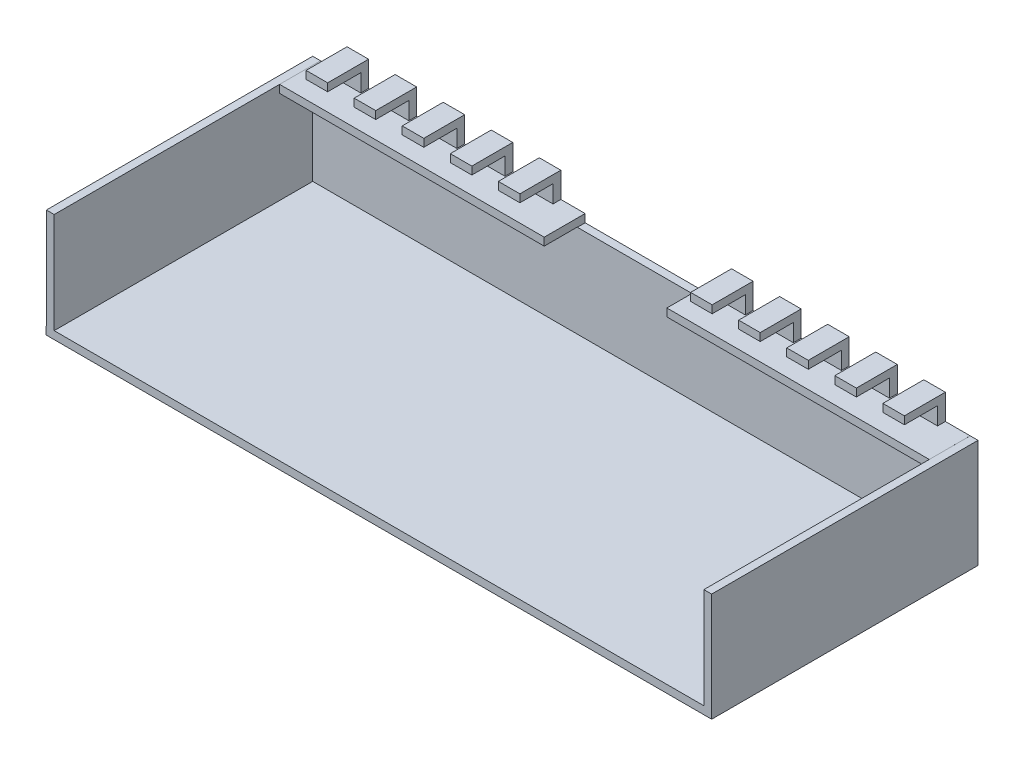
SolidWorks part; units mm, degrees
ref_plane "Plan de face" through (0, 0, 0) normal (0, 0, 1) x (1, 0, 0)
ref_plane "Plan de dessus" through (0, 0, 0) normal (0, 1, 0) x (1, 0, 0)
ref_plane "Plan de droite" through (0, 0, 0) normal (1, 0, 0) x (0, 0, -1)
sketch "Esquisse1" plane through (0, 0, 0) normal (0, 0, 1) x (1, 0, 0)
  line L0 (0, 0) -> (122.5, 0)
  line L1 (122.5, 0) -> (122.5, -5.3)
  line L2 (122.5, -5.3) -> (-73.5, -5.3)
  line L3 (-73.5, -5.3) -> (-73.5, 0)
  line L4 (-73.5, 0) -> (0, 0)
  line L5 (-73.5, 0) -> (-73.5, 2.35)
  line L6 (-73.5, 2.35) -> (122.5, 2.35)
  line L7 (122.5, 2.35) -> (122.5, 0)
  line L8 (122.5, -5.3) -> (122.5, -7.65)
  line L9 (122.5, -7.65) -> (-73.5, -7.65)
  line L10 (-73.5, -7.65) -> (-73.5, -5.3)
  dimension "D1" = 5.3
  dimension "D2" = 2.35
  dimension "D3" = 2.35
  dimension "D4" = 196
extrude "Boss.-Extru.1" add sketch "Esquisse1" along normal blind 10 contours L7 L6 L5 L4 L0 | L10 L9 L8 L2
sketch "Esquisse2" plane through (0, 0, 0) normal (0, 0, -1) x (-1, 0, 0)
  line L0 (-122.5, 2.35) -> (-122.5, -35.65)
  line L1 (73.5, 2.35) -> (73.5, -35.65)
  line L2 (73.5, -35.65) -> (-122.5, -35.65)
  line L3 (-122.5, 2.35) -> (73.5, 2.35)
  dimension "D1" = 38
extrude "Boss.-Extru.2" add sketch "Esquisse2" along normal blind 2.35
sketch "Esquisse3" plane through (-73.5, 0, 0) normal (-1, 0, 0) x (0, 0, 1)
  line L0 (-2.35, -5.3036) -> (78, -5.3036)
  line L1 (-2.35, -5.3036) -> (-2.35, -35.65)
  line L2 (-2.35, -35.65) -> (78, -35.65)
  line L3 (78, -35.65) -> (78, -5.3036)
  dimension "D1" = 80.35
extrude "Boss.-Extru.4" add sketch "Esquisse3" along normal blind 2.35
sketch "Esquisse5" plane through (122.5, 0, 0) normal (1, 0, 0) x (0, 0, -1)
  line L0 (-78, -5.3) -> (2.35, -5.3036)
  line L1 (2.35, -5.3036) -> (2.35, -35.65)
  line L2 (2.35, -35.65) -> (-78, -35.65)
  line L3 (-78, -35.65) -> (-78, -5.3)
  dimension "D1" = 80.35
extrude "Boss.-Extru.5" add sketch "Esquisse5" along normal blind 2.35
sketch "Esquisse6" plane through (0, 0, 10) normal (0, 0, 1) x (1, 0, 0)
  line L0 (-75.9651, -35.65) -> (-75.9651, -38)
  line L1 (124.85, -35.65) -> (-75.9651, -35.65)
  line L2 (-75.9651, -38) -> (124.85, -38)
  line L3 (124.85, -38) -> (124.85, -35.65)
  line L6 (124.85, -5.3) -> (124.85, -35.65) construction
  dimension "D1" = 2.35
  dimension "D2" = 0
extrude "Boss.-Extru.6" add sketch "Esquisse6" against normal blind 12.35 and the other way blind 68
sketch "Esquisse7" plane through (0, 0, 10) normal (0, 0, 1) x (1, 0, 0)
  line L0 (-73.5, 2.35) -> (-73.5, -5.3)
  line L1 (-73.5, -5.3) -> (-65.5, -5.3)
  line L2 (122.5, -5.3) -> (-73.5, -5.3) construction
  line L3 (-65.5, -5.3) -> (-65.5, 2.35)
  line L4 (-73.5, 2.35) -> (122.5, 2.35) construction
  line L5 (-65.5, 2.35) -> (-73.5, 2.35)
  line L6 (-51, 2.35) -> (-59, 2.35)
  line L7 (-59, 2.35) -> (-59, -5.3)
  line L8 (-59, -5.3) -> (-51, -5.3)
  line L9 (-51, -5.3) -> (-51, 2.35)
  line L10 (-36.5, 2.35) -> (-44.5, 2.35)
  line L11 (-44.5, 2.35) -> (-44.5, -5.3)
  line L12 (-44.5, -5.3) -> (-36.5, -5.3)
  line L13 (-36.5, -5.3) -> (-36.5, 2.35)
  line L14 (-22, 2.35) -> (-30, 2.35)
  line L15 (-30, 2.35) -> (-30, -5.3)
  line L16 (-30, -5.3) -> (-22, -5.3)
  line L17 (-22, -5.3) -> (-22, 2.35)
  line L18 (-7.5, 2.35) -> (-15.5, 2.35)
  line L19 (-15.5, 2.35) -> (-15.5, -5.3)
  line L20 (-15.5, -5.3) -> (-7.5, -5.3)
  line L21 (-7.5, -5.3) -> (-7.5, 2.35)
  line L22 (7, 2.35) -> (-1, 2.35)
  line L23 (-1, 2.35) -> (-1, -5.3)
  line L24 (-1, -5.3) -> (7, -5.3)
  line L25 (7, -5.3) -> (7, 2.35)
  line L26 (21.5, 2.35) -> (13.5, 2.35)
  line L27 (13.5, 2.35) -> (13.5, -5.3)
  line L28 (13.5, -5.3) -> (21.5, -5.3)
  line L29 (21.5, -5.3) -> (21.5, 2.35)
  line L30 (36, 2.35) -> (28, 2.35)
  line L31 (28, 2.35) -> (28, -5.3)
  line L32 (28, -5.3) -> (36, -5.3)
  line L33 (36, -5.3) -> (36, 2.35)
  line L34 (50.5, 2.35) -> (42.5, 2.35)
  line L35 (42.5, 2.35) -> (42.5, -5.3)
  line L36 (42.5, -5.3) -> (50.5, -5.3)
  line L37 (50.5, -5.3) -> (50.5, 2.35)
  line L38 (65, 2.35) -> (57, 2.35)
  line L39 (57, 2.35) -> (57, -5.3)
  line L40 (57, -5.3) -> (65, -5.3)
  line L41 (65, -5.3) -> (65, 2.35)
  line L42 (79.5, 2.35) -> (71.5, 2.35)
  line L43 (71.5, 2.35) -> (71.5, -5.3)
  line L44 (71.5, -5.3) -> (79.5, -5.3)
  line L45 (79.5, -5.3) -> (79.5, 2.35)
  line L46 (94, 2.35) -> (86, 2.35)
  line L47 (86, 2.35) -> (86, -5.3)
  line L48 (86, -5.3) -> (94, -5.3)
  line L49 (94, -5.3) -> (94, 2.35)
  line L50 (108.5, 2.35) -> (100.5, 2.35)
  line L51 (100.5, 2.35) -> (100.5, -5.3)
  line L52 (100.5, -5.3) -> (108.5, -5.3)
  line L53 (108.5, -5.3) -> (108.5, 2.35)
  line L54 (123, 2.35) -> (115, 2.35)
  line L55 (115, 2.35) -> (115, -5.3)
  line L56 (115, -5.3) -> (123, -5.3)
  line L57 (123, -5.3) -> (123, 2.35)
  line L58 (137.5, 2.35) -> (129.5, 2.35)
  line L59 (129.5, 2.35) -> (129.5, -5.3)
  line L60 (129.5, -5.3) -> (137.5, -5.3)
  line L61 (137.5, -5.3) -> (137.5, 2.35)
  line L62 (152, 2.35) -> (144, 2.35)
  line L63 (144, 2.35) -> (144, -5.3)
  line L64 (144, -5.3) -> (152, -5.3)
  line L65 (152, -5.3) -> (152, 2.35)
  line L66 (166.5, 2.35) -> (158.5, 2.35)
  line L67 (158.5, 2.35) -> (158.5, -5.3)
  line L68 (158.5, -5.3) -> (166.5, -5.3)
  line L69 (166.5, -5.3) -> (166.5, 2.35)
  line L70 (181, 2.35) -> (173, 2.35)
  line L71 (173, 2.35) -> (173, -5.3)
  line L72 (173, -5.3) -> (181, -5.3)
  line L73 (181, -5.3) -> (181, 2.35)
  line L74 (195.5, 2.35) -> (187.5, 2.35)
  line L75 (187.5, 2.35) -> (187.5, -5.3)
  line L76 (187.5, -5.3) -> (195.5, -5.3)
  line L77 (195.5, -5.3) -> (195.5, 2.35)
  line L78 (210, 2.35) -> (202, 2.35)
  line L79 (202, 2.35) -> (202, -5.3)
  line L80 (202, -5.3) -> (210, -5.3)
  line L81 (210, -5.3) -> (210, 2.35)
  line L82 (224.5, 2.35) -> (216.5, 2.35)
  line L83 (216.5, 2.35) -> (216.5, -5.3)
  line L84 (216.5, -5.3) -> (224.5, -5.3)
  line L85 (224.5, -5.3) -> (224.5, 2.35)
  line L86 (239, 2.35) -> (231, 2.35)
  line L87 (231, 2.35) -> (231, -5.3)
  line L88 (231, -5.3) -> (239, -5.3)
  line L89 (239, -5.3) -> (239, 2.35)
  line L90 (253.5, 2.35) -> (245.5, 2.35)
  line L91 (245.5, 2.35) -> (245.5, -5.3)
  line L92 (245.5, -5.3) -> (253.5, -5.3)
  line L93 (253.5, -5.3) -> (253.5, 2.35)
  line L94 (268, 2.35) -> (260, 2.35)
  line L95 (260, 2.35) -> (260, -5.3)
  line L96 (260, -5.3) -> (268, -5.3)
  line L97 (268, -5.3) -> (268, 2.35)
  line L98 (282.5, 2.35) -> (274.5, 2.35)
  line L99 (274.5, 2.35) -> (274.5, -5.3)
  line L100 (274.5, -5.3) -> (282.5, -5.3)
  line L101 (282.5, -5.3) -> (282.5, 2.35)
  line L102 (297, 2.35) -> (289, 2.35)
  line L103 (289, 2.35) -> (289, -5.3)
  line L104 (289, -5.3) -> (297, -5.3)
  line L105 (297, -5.3) -> (297, 2.35)
  line L106 (311.5, 2.35) -> (303.5, 2.35)
  line L107 (303.5, 2.35) -> (303.5, -5.3)
  line L108 (303.5, -5.3) -> (311.5, -5.3)
  line L109 (311.5, -5.3) -> (311.5, 2.35)
  line L110 (326, 2.35) -> (318, 2.35)
  line L111 (318, 2.35) -> (318, -5.3)
  line L112 (318, -5.3) -> (326, -5.3)
  line L113 (326, -5.3) -> (326, 2.35)
  line L114 (340.5, 2.35) -> (332.5, 2.35)
  line L115 (332.5, 2.35) -> (332.5, -5.3)
  line L116 (332.5, -5.3) -> (340.5, -5.3)
  line L117 (340.5, -5.3) -> (340.5, 2.35)
  line L118 (355, 2.35) -> (347, 2.35)
  line L119 (347, 2.35) -> (347, -5.3)
  line L120 (347, -5.3) -> (355, -5.3)
  line L121 (355, -5.3) -> (355, 2.35)
  line L122 (369.5, 2.35) -> (361.5, 2.35)
  line L123 (361.5, 2.35) -> (361.5, -5.3)
  line L124 (361.5, -5.3) -> (369.5, -5.3)
  line L125 (369.5, -5.3) -> (369.5, 2.35)
  line L126 (384, 2.35) -> (376, 2.35)
  line L127 (376, 2.35) -> (376, -5.3)
  line L128 (376, -5.3) -> (384, -5.3)
  line L129 (384, -5.3) -> (384, 2.35)
  line L130 (398.5, 2.35) -> (390.5, 2.35)
  line L131 (390.5, 2.35) -> (390.5, -5.3)
  line L132 (390.5, -5.3) -> (398.5, -5.3)
  line L133 (398.5, -5.3) -> (398.5, 2.35)
  line L134 (413, 2.35) -> (405, 2.35)
  line L135 (405, 2.35) -> (405, -5.3)
  line L136 (405, -5.3) -> (413, -5.3)
  line L137 (413, -5.3) -> (413, 2.35)
  line L138 (427.5, 2.35) -> (419.5, 2.35)
  line L139 (419.5, 2.35) -> (419.5, -5.3)
  line L140 (419.5, -5.3) -> (427.5, -5.3)
  line L141 (427.5, -5.3) -> (427.5, 2.35)
  line L142 (442, 2.35) -> (434, 2.35)
  line L143 (434, 2.35) -> (434, -5.3)
  line L144 (434, -5.3) -> (442, -5.3)
  line L145 (442, -5.3) -> (442, 2.35)
  line L146 (456.5, 2.35) -> (448.5, 2.35)
  line L147 (448.5, 2.35) -> (448.5, -5.3)
  line L148 (448.5, -5.3) -> (456.5, -5.3)
  line L149 (456.5, -5.3) -> (456.5, 2.35)
  line L150 (471, 2.35) -> (463, 2.35)
  line L151 (463, 2.35) -> (463, -5.3)
  line L152 (463, -5.3) -> (471, -5.3)
  line L153 (471, -5.3) -> (471, 2.35)
  line L154 (485.5, 2.35) -> (477.5, 2.35)
  line L155 (477.5, 2.35) -> (477.5, -5.3)
  line L156 (477.5, -5.3) -> (485.5, -5.3)
  line L157 (485.5, -5.3) -> (485.5, 2.35)
  line L158 (500, 2.35) -> (492, 2.35)
  line L159 (492, 2.35) -> (492, -5.3)
  line L160 (492, -5.3) -> (500, -5.3)
  line L161 (500, -5.3) -> (500, 2.35)
  line L162 (514.5, 2.35) -> (506.5, 2.35)
  line L163 (506.5, 2.35) -> (506.5, -5.3)
  line L164 (506.5, -5.3) -> (514.5, -5.3)
  line L165 (514.5, -5.3) -> (514.5, 2.35)
  line L166 (529, 2.35) -> (521, 2.35)
  line L167 (521, 2.35) -> (521, -5.3)
  line L168 (521, -5.3) -> (529, -5.3)
  line L169 (529, -5.3) -> (529, 2.35)
  line L170 (543.5, 2.35) -> (535.5, 2.35)
  line L171 (535.5, 2.35) -> (535.5, -5.3)
  line L172 (535.5, -5.3) -> (543.5, -5.3)
  line L173 (543.5, -5.3) -> (543.5, 2.35)
  line L174 (558, 2.35) -> (550, 2.35)
  line L175 (550, 2.35) -> (550, -5.3)
  line L176 (550, -5.3) -> (558, -5.3)
  line L177 (558, -5.3) -> (558, 2.35)
  line L178 (572.5, 2.35) -> (564.5, 2.35)
  line L179 (564.5, 2.35) -> (564.5, -5.3)
  line L180 (564.5, -5.3) -> (572.5, -5.3)
  line L181 (572.5, -5.3) -> (572.5, 2.35)
  line L182 (587, 2.35) -> (579, 2.35)
  line L183 (579, 2.35) -> (579, -5.3)
  line L184 (579, -5.3) -> (587, -5.3)
  line L185 (587, -5.3) -> (587, 2.35)
  line L186 (601.5, 2.35) -> (593.5, 2.35)
  line L187 (593.5, 2.35) -> (593.5, -5.3)
  line L188 (593.5, -5.3) -> (601.5, -5.3)
  line L189 (601.5, -5.3) -> (601.5, 2.35)
  line L190 (616, 2.35) -> (608, 2.35)
  line L191 (608, 2.35) -> (608, -5.3)
  line L192 (608, -5.3) -> (616, -5.3)
  line L193 (616, -5.3) -> (616, 2.35)
  line L194 (630.5, 2.35) -> (622.5, 2.35)
  line L195 (622.5, 2.35) -> (622.5, -5.3)
  line L196 (622.5, -5.3) -> (630.5, -5.3)
  line L197 (630.5, -5.3) -> (630.5, 2.35)
  line L198 (645, 2.35) -> (637, 2.35)
  line L199 (637, 2.35) -> (637, -5.3)
  line L200 (637, -5.3) -> (645, -5.3)
  line L201 (645, -5.3) -> (645, 2.35)
  dimension "D1" = 8
  dimension "D2" = 50
extrude "Enlèv. mat.-Extru.1" cut sketch "Esquisse7" against normal blind 13
sketch "Esquisse9" plane through (0, 0, 10) normal (0, 0, 1) x (1, 0, 0)
  line L0 (6.3382, 4.2746) -> (6.3382, -7.7254)
  line L2 (43.3382, 4.2746) -> (43.3382, -7.7254)
  line L3 (43.3382, -7.7254) -> (6.3382, -7.7254)
  line L4 (6.3382, 4.2746) -> (43.3382, 4.2746)
  line L5 (-75.85, -5.3036) -> (124.85, -5.3) construction
  line L6 (6.3382, 4.2746) -> (43.3382, 4.2746) construction
  dimension "D1" = 12
extrude "Enlèv. mat.-Extru.2" cut sketch "Esquisse9" against normal blind 13 contours L4 L2 L3 L0
